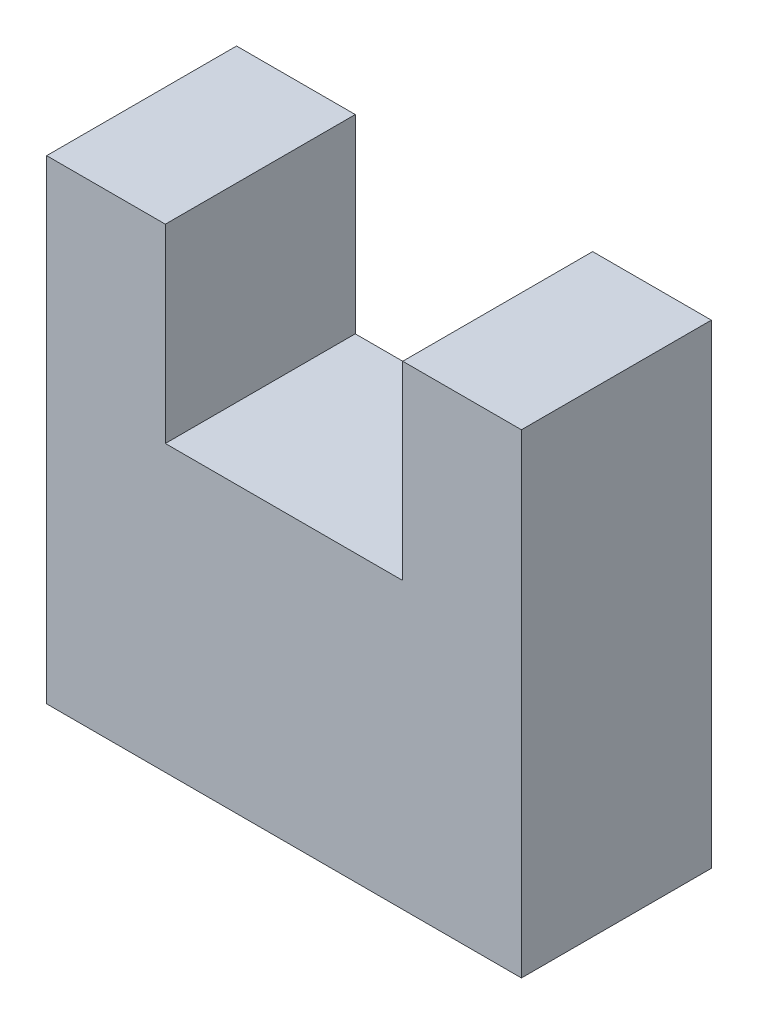
SolidWorks part; units mm, degrees
ref_plane "Ebene vorne" through (0, 0, 0) normal (0, 0, 1) x (1, 0, 0)
ref_plane "Ebene oben" through (0, 0, 0) normal (0, 1, 0) x (1, 0, 0)
ref_plane "Ebene rechts" through (0, 0, 0) normal (1, 0, 0) x (0, 0, -1)
sketch "Skizze1" plane through (0, 0, 0) normal (0, 0, 1) x (1, 0, 0)
  line L0 (50, 0) -> (-50, 0)
  line L1 (-50, 0) -> (-50, 100)
  line L2 (-50, 100) -> (-25, 100)
  line L3 (-25, 100) -> (-25, 60)
  line L4 (-25, 60) -> (25, 60)
  line L6 (0, 60) -> (0, 0) construction
  line L7 (25, 100) -> (25, 60)
  line L8 (50, 100) -> (25, 100)
  line L9 (50, 0) -> (50, 100)
  dimension "D1" = 100
  dimension "D2" = 100
  dimension "D3" = 40
  dimension "D4" = 50
extrude "Aufsatz-Linear austragen1" add sketch "Skizze1" along normal blind 40
